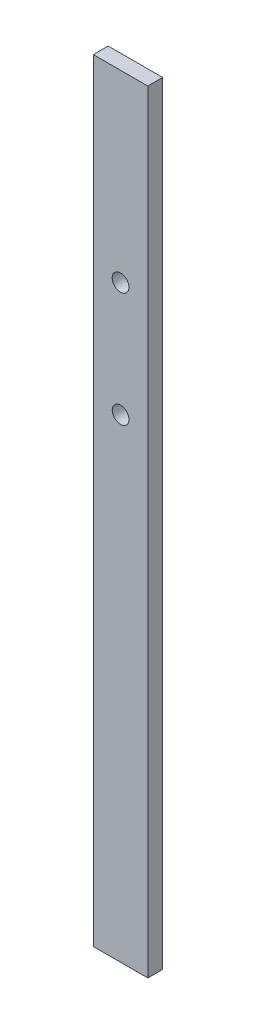
SolidWorks part; units mm, degrees
ref_plane "Front Plane" through (0, 0, 0) normal (0, 0, 1) x (1, 0, 0)
ref_plane "Top Plane" through (0, 0, 0) normal (0, 1, 0) x (1, 0, 0)
ref_plane "Right Plane" through (0, 0, 0) normal (1, 0, 0) x (0, 0, -1)
sketch "Sketch1" plane through (0, 0, 0) normal (0, 1, 0) x (1, 0, 0)
  line L1 (-69.85, -19.05) -> (69.85, -19.05)
  line L2 (-69.85, -19.05) -> (-69.85, 19.05)
  line L3 (-69.85, 19.05) -> (69.85, 19.05)
  line L4 (69.85, -19.05) -> (69.85, 19.05)
  line L5 (-69.85, -19.05) -> (69.85, 19.05) construction
  line L6 (-69.85, 19.05) -> (69.85, -19.05) construction
  point P0 (0, 0)
  dimension "D1" = 38.1
  dimension "D2" = 139.7
extrude "Boss-Extrude1" add sketch "Sketch1" along normal blind 1981.2
hole_wizard "1 (1.6875) Diameter Hole1" positions "Sketch2" profile "Sketch3" hole size "1" standard "ANSI Inch" end condition through all
sketch "Sketch2" plane through (0, 0, -19.05) normal (0, 0, -1) x (-1, 0, 0)
  line L0 (-69.85, 0) -> (69.85, 0) construction
  line L1 (-69.85, 1981.2) -> (-69.85, 0) construction
  point P0 (0, 1216.025)
  point P6 (0, 1509.7125)
  dimension "D1" = 1216.025
  dimension "D2" = 69.85
  dimension "D3" = 1509.7125
sketch "Sketch3" plane through (0, 1216.025, -19.05) normal (1, 0, 0) x (0, 1, 0)
  line L0 (0, 0) -> (0, 38.1)
  line L1 (0, 38.1) -> (21.4312, 38.1)
  line L2 (21.4312, 38.1) -> (21.4312, 0)
  line L5 (21.4312, 0) -> (0, 0)
  line L11 (0, -6.35) -> (0, 107.95) construction
  dimension "Thru Hole Dia." = 42.8625
  dimension "Thru Hole Depth" = 38.1
